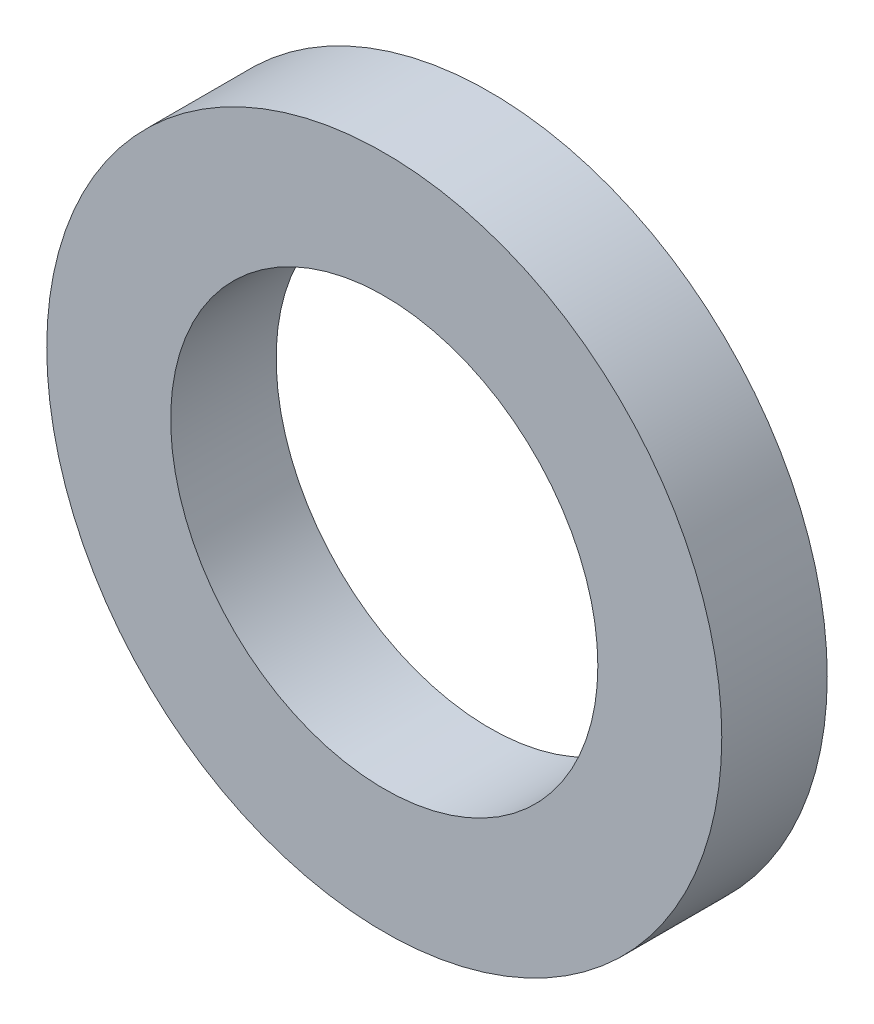
SolidWorks part; units mm, degrees
ref_plane "Plan de face" through (0, 0, 0) normal (0, 0, 1) x (1, 0, 0)
ref_plane "Plan de dessus" through (0, 0, 0) normal (0, 1, 0) x (1, 0, 0)
ref_plane "Plan de droite" through (0, 0, 0) normal (1, 0, 0) x (0, 0, -1)
sketch "Esquisse2" plane through (0, 0, 0) normal (0, 0, 1) x (1, 0, 0)
  circle A0 centre (0, 0) radius 4.05
  circle A1 centre (0, 0) radius 6.4
  dimension "D1" = 12.8
  dimension "D2" = 8.1
extrude "Boss.-Extru.1" add sketch "Esquisse2" along normal blind 2
